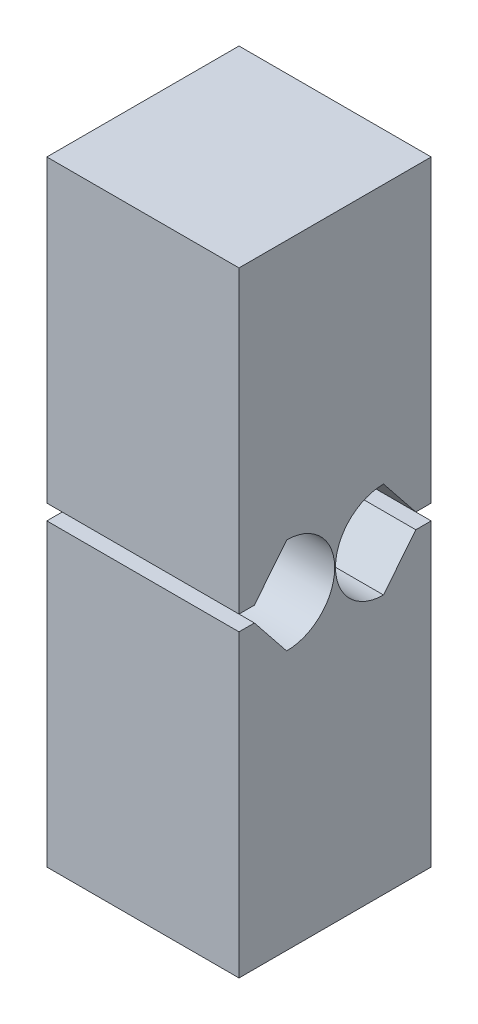
SolidWorks part; units mm, degrees
material "Beryllium Copper, UNS C17300"
ref_plane "Front Plane" through (0, 0, 0) normal (0, 0, 1) x (1, 0, 0)
ref_plane "Top Plane" through (0, 0, 0) normal (0, 1, 0) x (1, 0, 0)
ref_plane "Right Plane" through (0, 0, 0) normal (1, 0, 0) x (0, 0, -1)
sketch "Sketch1" plane through (0, 0, 0) normal (0, 1, 0) x (1, 0, 0)
  line L1 (-3.175, 3.175) -> (3.175, 3.175)
  line L2 (-3.175, 3.175) -> (-3.175, -3.175)
  line L3 (-3.175, -3.175) -> (3.175, -3.175)
  line L4 (3.175, 3.175) -> (3.175, -3.175)
  dimension "D1" = 3.175
  dimension "D2" = 3.175
  dimension "D3" = 3.175
  dimension "D4" = 3.175
extrude "Boss-Extrude1" add sketch "Sketch1" along normal mid plane 20.32
sketch "Sketch2" plane through (3.175, 0, 0) normal (1, 0, 0) x (0, 0, -1)
  line L0 (-3.175, 0.254) -> (-3.175, -0.254)
  line L1 (-3.175, 10.16) -> (-3.175, -10.16) construction
  line L2 (-3.175, -0.254) -> (-2.667, -0.254)
  line L3 (-2.667, -0.254) -> (-1.6002, -1.5875)
  line L4 (-3.175, 0.254) -> (-2.667, 0.254)
  line L5 (-2.667, 0.254) -> (-1.6002, 1.5875)
  arc A0 (-1.6002, 1.5875) -> (-1.6002, -1.5875) centre (-1.6002, 0) cw
  dimension "D1" = 0.254
  dimension "D2" = 0.254
  dimension "D3" = 0.508
  dimension "D4" = 0.508
extrude "Cut-Extrude1" cut sketch "Sketch2" against normal up to next
mirror "Mirror1" about plane through (0, 0, 0) normal (0, 0, 1) of "Cut-Extrude1"
